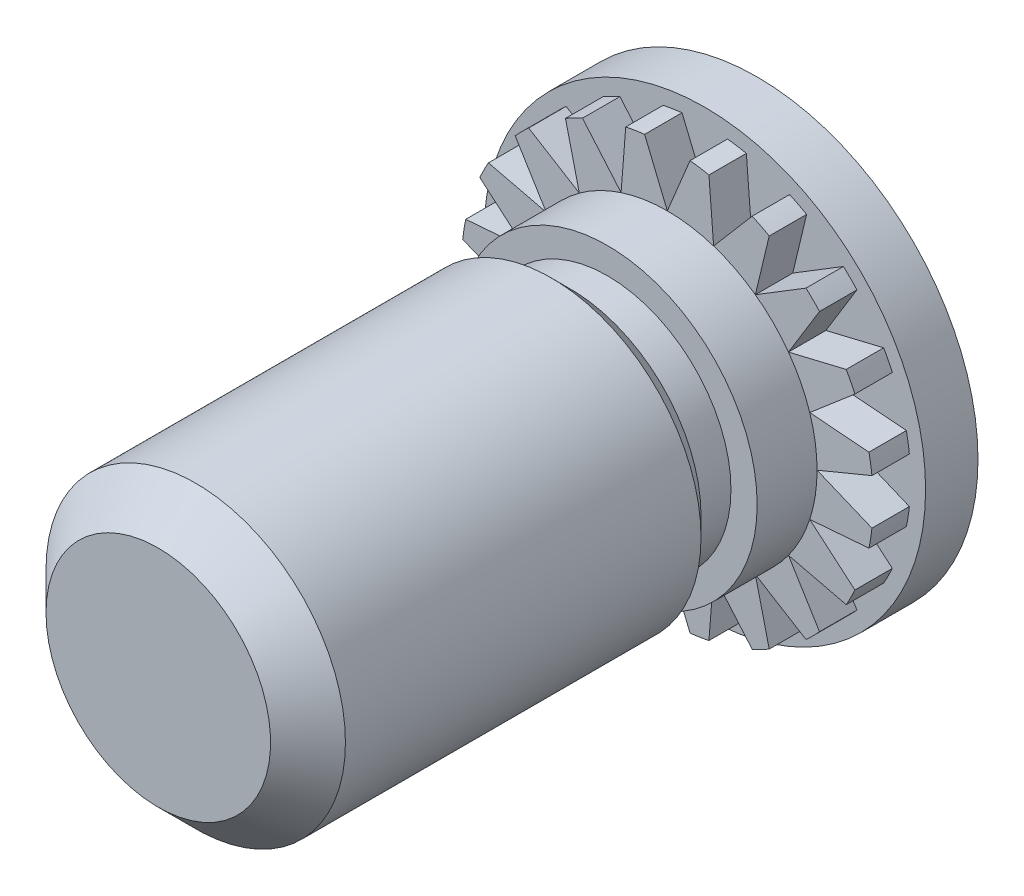
SolidWorks part; units mm, degrees
ref_plane "Спереди" through (0, 0, 0) normal (0, 0, 1) x (1, 0, 0)
ref_plane "Сверху" through (0, 0, 0) normal (0, 1, 0) x (1, 0, 0)
ref_plane "Справа" through (0, 0, 0) normal (1, 0, 0) x (0, 0, -1)
sketch "Эскиз1" plane through (0, 0, 0) normal (0, 0, 1) x (1, 0, 0)
  circle A0 centre (0, 0) radius 2.95
  dimension "D1" = 5.9
extrude "Вытянуть1" add sketch "Эскиз1" along normal blind 1.2
ref_axis "Ось1" through (0, 0, 10.6426) along (0, 0, -1)
sketch "Эскиз2" plane through (0, 0, 1.2) normal (0, 0, 1) x (1, 0, 0)
  circle A0 centre (0, 0) radius 2
  dimension "D1" = 4
extrude "Вытянуть2" add sketch "Эскиз2" along normal blind 1.9
sketch "Эскиз3" plane through (0, 0, 1.2) normal (0, 0, 1) x (1, 0, 0)
  line L0 (0, 0) -> (0, 2.95) construction
  line L1 (-0.3935, 2.95) -> (0.3935, 2.95)
  line L2 (0.3935, 2.95) -> (0, 2)
  line L3 (0, 2) -> (-0.3935, 2.95)
  circle A0 centre (0, 0) radius 2.95 construction
  circle A1 centre (0, 0) radius 2 construction
  dimension "D1" = 45
extrude "Вырез-Вытянуть1" cut sketch "Эскиз3" against normal blind 0.5
pattern_circular "Круговой массив1" count 20 over 360 about axis through (0, 0, 0) along (0, 0, 1) of "Вырез-Вытянуть1"
sketch "Эскиз4" plane through (0, 0, 0) normal (0, 1, 0) x (1, 0, 0)
  line L0 (0, -2.25) -> (2, -2.25) construction
  line L1 (0, -10.6426) -> (0, 0.6656) construction
  line L2 (-2, -3.1) -> (2, -3.1) construction
  line L3 (2, -2) -> (1.65, -2)
  line L4 (2, -2) -> (2, -2.5)
  line L5 (2, -2.5) -> (1.65, -2.5)
  line L6 (1.65, -2) -> (1.65, -2.5)
  dimension "D1" = 0.5
  dimension "D2" = 0.6
  dimension "D3" = 2
  dimension "D4" = 0.35
revolve "Вырез-Повернуть1" cut sketch "Эскиз4" angle 360 about axis through (0, 0, 10.6426) along (0, 0, -1)
sketch "Эскиз6" plane through (0, 0, 0) normal (1, 0, 0) x (0, 0, -1)
  line L0 (-3.1, 0) -> (-8, 0)
  line L1 (-3.1, 2) -> (-3.1, -2) construction
  line L2 (-10.6426, 0) -> (0.6656, 0) construction
  line L3 (-8, 0) -> (-8, -2)
  line L4 (-8, -2) -> (-3.1, -2)
  line L5 (-3.1, -2) -> (-3.1, 0)
  line L6 (0, -2.95) -> (0, 2.95) construction
  dimension "D1" = 8
  dimension "D2" = 2
revolve "Повернуть1" add sketch "Эскиз6" angle 360 about L0
chamfer "Фаска2" distance 0.5 angle 45 1 edges at (-2, 0, 8)
sketch "Эскиз7" plane through (0, 0, 1.2) normal (0, 0, 1) x (1, 0, 0)
  circle A0 centre (0, 0) radius 2.75
  circle A1 centre (0, 0) radius 2.95
  arc A2 (-1.4093, 2.5916) -> (-2.0293, 2.1412) centre (0, 0) ccw construction
  dimension "D1" = 0.2
extrude "Вырез-Вытянуть2" cut sketch "Эскиз7" against normal up to surface (0.5 mm away) up to face at (-2.4965, 0.8112, 0.7)
chamfer "Фаска3" distance 0.25 angle 45 1 edges at (2, 0, 2.5)
